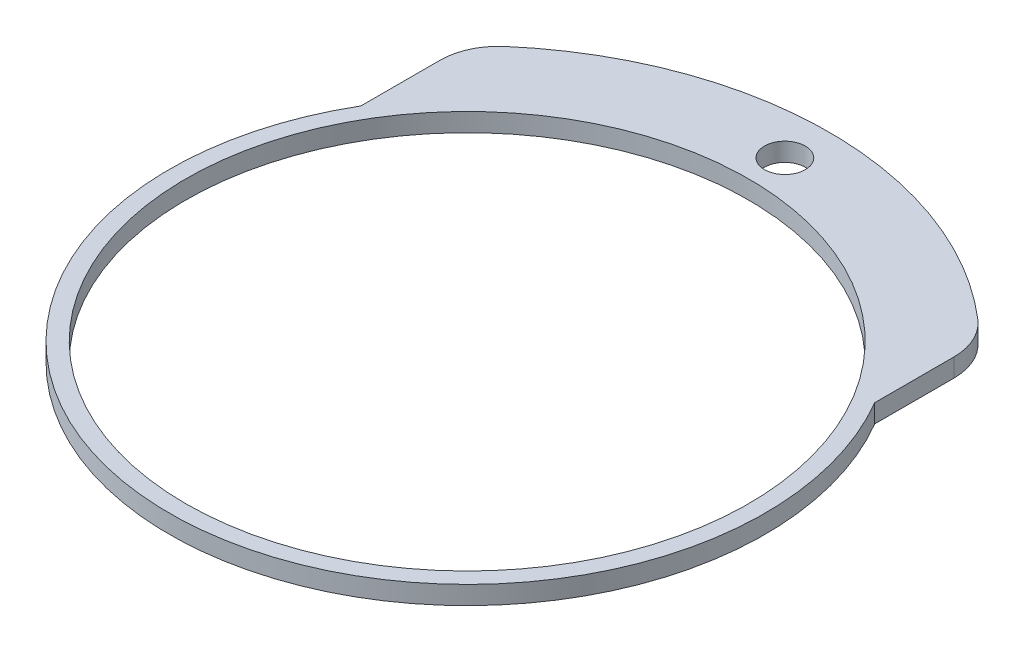
SolidWorks part; units mm, degrees
ref_plane "Front Plane" through (0, 0, 0) normal (0, 0, 1) x (1, 0, 0)
ref_plane "Top Plane" through (0, 0, 0) normal (0, 1, 0) x (1, 0, 0)
ref_plane "Right Plane" through (0, 0, 0) normal (1, 0, 0) x (0, 0, -1)
sketch "Sketch1" plane through (0, 0, 0) normal (0, 1, 0) x (1, 0, 0)
  line L0 (-27.94, 16.3751) -> (-27.94, 27.7372)
  line L1 (27.94, 16.3751) -> (27.94, 27.7372)
  circle A0 centre (0, 0) radius 32.385
  arc A1 (-27.94, 27.7372) -> (27.94, 27.7372) centre (0, 0) cw
  dimension "D3" = 64.77
  dimension "D4" = 39.37
  dimension "D1" = 27.94
  dimension "D2" = 55.88
extrude "Boss-Extrude1" add sketch "Sketch1" along normal blind 2 contours A0 | A1 L0 A0 L1
fillet "Fillet1" radius 6.35 2 edges at (27.94, 1, -27.7372) (-27.94, 1, -27.7372)
sketch "Sketch2" plane through (0, 2, 0) normal (0, 1, 0) x (1, 0, 0)
  line L0 (27.94, 16.3751) -> (27.94, 24.9838) construction
  circle A2 centre (0, 34.544) radius 2.2225
  dimension "D7" = 4.445
  dimension "D8" = 34.544
  dimension "D9" = 27.94
extrude "Cut-Extrude1" cut sketch "Sketch2" against normal through all
sketch "Sketch3" plane through (0, 2, 0) normal (0, 1, 0) x (1, 0, 0)
  circle A0 centre (0, 0) radius 30.6
extrude "Cut-Extrude2" cut sketch "Sketch3" against normal through all
